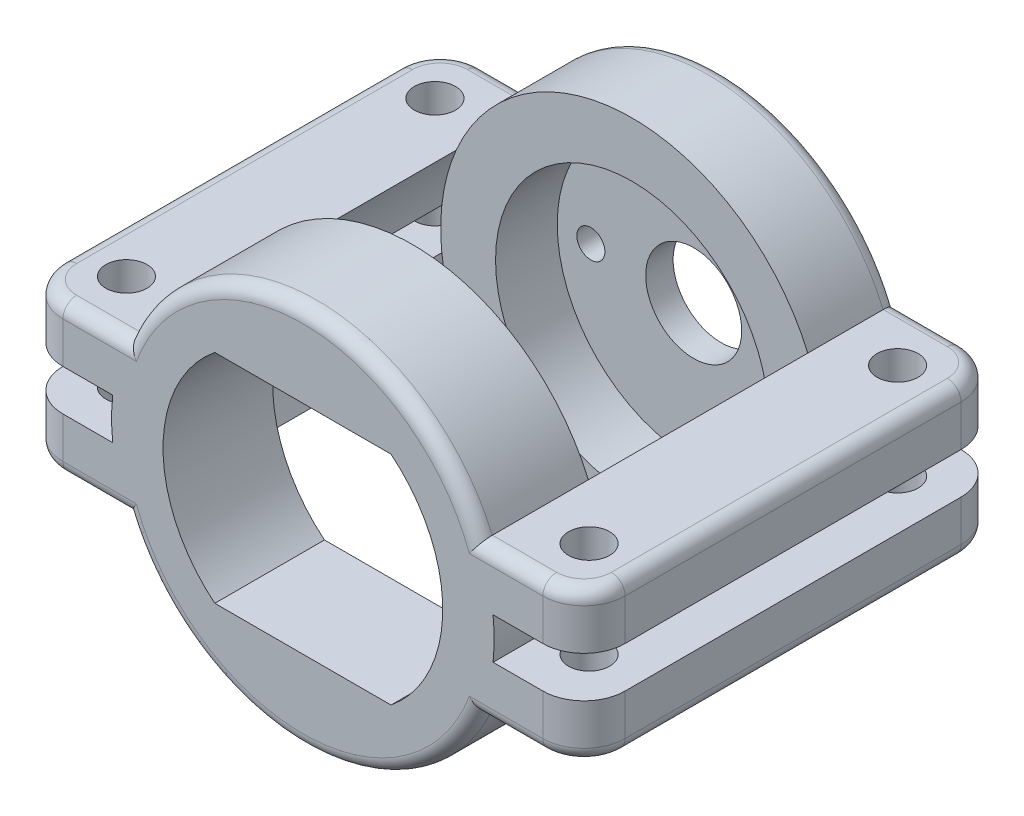
SolidWorks part; units mm, degrees
ref_plane "Alzado" through (0, 0, 0) normal (0, 0, 1) x (1, 0, 0)
ref_plane "Planta" through (0, 0, 0) normal (0, 1, 0) x (1, 0, 0)
ref_plane "Vista lateral" through (0, 0, 0) normal (1, 0, 0) x (0, 0, -1)
sketch "Croquis1" plane through (0, 0, 0) normal (0, 0, 1) x (1, 0, 0)
  line L0 (0, 1.5) -> (0, -1.5) construction
  line L1 (-13.8691, 1.5) -> (-24, 1.5)
  line L2 (-24, 1.5) -> (-24, 5.5)
  line L3 (-13.8691, -1.5) -> (-24, -1.5)
  line L4 (-24, 5.5) -> (-12.82, 5.5)
  line L5 (-24, -1.5) -> (-24, -5.5)
  line L6 (-24, -5.5) -> (-12.82, -5.5)
  line L7 (24, -5.5) -> (12.82, -5.5)
  line L8 (24, 5.5) -> (12.82, 5.5)
  line L9 (13.8691, -1.5) -> (24, -1.5)
  line L10 (13.8691, 1.5) -> (24, 1.5)
  line L11 (24, -1.5) -> (24, -5.5)
  line L12 (24, 1.5) -> (24, 5.5)
  arc A0 (12.82, 5.5) -> (-12.82, 5.5) centre (0, 0) ccw
  arc A1 (-13.8691, 1.5) -> (-13.8691, -1.5) centre (0, 0) ccw
  arc A2 (-12.82, -5.5) -> (12.82, -5.5) centre (0, 0) ccw
  arc A3 (13.8691, -1.5) -> (13.8691, 1.5) centre (0, 0) ccw
  dimension "D2" = 10.1309
  dimension "D3" = 10.1309
  dimension "D4" = 11.18
  dimension "D5" = 11.18
  dimension "D6" = 4
  dimension "D7" = 4
extrude "Saliente-Extruir1" add sketch "Croquis1" along normal blind 6.5
sketch "Croquis2" plane through (0, 0, 6.5) normal (0, 0, 1) x (1, 0, 0)
  circle A0 centre (0, 0) radius 9.95
  dimension "D1" = 19.9
extrude "Cortar-Extruir1" cut sketch "Croquis2" against normal blind 4.5
sketch "Croquis3" plane through (0, 0, 2) normal (0, 0, 1) x (1, 0, 0)
  line L0 (0, 9.95) -> (0, -9.95) construction
  line L1 (-9.95, 0) -> (9.95, 0) construction
  circle A0 centre (0, 0) radius 3.5
  circle A1 centre (0, 0) radius 9.95 construction
  circle A4 centre (-7.5, 0) radius 1.025
  circle A5 centre (7.5, 0) radius 1.025
  dimension "D1" = 7
  dimension "D2" = 2.05
  dimension "D3" = 2.05
  dimension "D4" = 7.5
  dimension "D5" = 7.5
extrude "Cortar-Extruir2" cut sketch "Croquis3" against normal blind 3.5
sketch "Croquis4" plane through (0, 0, 6.5) normal (0, 0, 1) x (1, 0, 0)
  line L2 (-12.82, 5.5) -> (-24, 5.5)
  line L3 (-24, 5.5) -> (-24, 1.5)
  line L4 (-24, 1.5) -> (-13.8691, 1.5)
  line L5 (-13.8691, -1.5) -> (-24, -1.5)
  line L6 (-24, -1.5) -> (-24, -5.5)
  line L7 (-24, -5.5) -> (-12.82, -5.5)
  line L8 (0, 9.95) -> (0, -9.95) construction
  line L9 (24, -5.5) -> (12.82, -5.5)
  line L10 (24, -1.5) -> (24, -5.5)
  line L11 (13.8691, -1.5) -> (24, -1.5)
  line L12 (24, 1.5) -> (13.8691, 1.5)
  line L13 (24, 5.5) -> (24, 1.5)
  line L14 (12.82, 5.5) -> (24, 5.5)
  arc A0 (-12.82, 5.5) -> (-13.8691, 1.5) centre (0, 0) ccw
  arc A1 (12.82, 5.5) -> (-12.82, 5.5) centre (0, 0) ccw construction
  arc A2 (-13.8691, -1.5) -> (-12.82, -5.5) centre (0, 0) ccw
  arc A3 (-13.8691, 1.5) -> (-13.8691, -1.5) centre (0, 0) ccw construction
  circle A4 centre (0, 0) radius 9.95 construction
  arc A5 (13.8691, -1.5) -> (12.82, -5.5) centre (0, 0) cw
  arc A6 (12.82, 5.5) -> (13.8691, 1.5) centre (0, 0) cw
extrude "Saliente-Extruir2" add sketch "Croquis4" along normal blind 16
sketch "Croquis6" plane through (0, 0, 22.5) normal (0, 0, 1) x (1, 0, 0)
  line L0 (-12.82, 5.5) -> (-24, 5.5)
  line L1 (-24, 5.5) -> (-24, 1.5)
  line L2 (-24, 1.5) -> (-13.8691, 1.5)
  line L4 (24, -1.5) -> (13.8691, -1.5)
  line L5 (24, -5.5) -> (24, -1.5)
  line L6 (12.82, 5.5) -> (24, 5.5)
  line L7 (24, 5.5) -> (24, 1.5)
  line L8 (24, 1.5) -> (13.8691, 1.5)
  line L9 (12.82, -5.5) -> (24, -5.5)
  line L10 (-24, -1.5) -> (-13.8691, -1.5)
  line L11 (-24, -5.5) -> (-24, -1.5)
  line L12 (-12.82, -5.5) -> (-24, -5.5)
  arc A0 (12.82, 5.5) -> (-12.82, 5.5) centre (0, 0) ccw
  arc A3 (12.82, -5.5) -> (-12.82, -5.5) centre (0, 0) cw
  arc A4 (-13.8691, 1.5) -> (-13.8691, -1.5) centre (0, 0) ccw
  arc A5 (13.8691, -1.5) -> (13.8691, 1.5) centre (0, 0) ccw
  dimension "D5" = 3
  dimension "D6" = 3
  dimension "D1" = 4
  dimension "D2" = 4
  dimension "D3" = 10.1309
  dimension "D4" = 11.18
  dimension "D7" = 4
  dimension "D8" = 11.18
  dimension "D9" = 4
extrude "Saliente-Extruir3" add sketch "Croquis6" along normal blind 8
sketch "Croquis7" plane through (0, 0, 30.5) normal (0, 0, 1) x (1, 0, 0)
  line L0 (-6.425, 7.9221) -> (6.425, 7.9221)
  line L1 (-6.425, -7.9221) -> (6.425, -7.9221)
  arc A0 (-6.425, 7.9221) -> (-6.425, -7.9221) centre (0, 0) ccw
  arc A1 (6.425, -7.9221) -> (6.425, 7.9221) centre (0, 0) ccw
  dimension "D1" = 10.2
  dimension "D4" = 10.2
  dimension "D2" = 12.85
  dimension "D3" = 12.85
extrude "Cortar-Extruir3" cut sketch "Croquis7" against normal blind 8
sketch "Croquis8" plane through (0, 5.5, 0) normal (0, 1, 0) x (1, 0, 0)
  line L0 (12.82, -30.5) -> (12.82, -22.5) construction
  line L1 (12.82, -22.5) -> (24, -22.5) construction
  line L2 (24, -30.5) -> (24, 0) construction
  line L3 (12.82, 0) -> (12.82, -8) construction
  line L4 (12.82, -22.5) -> (12.82, -6.5) construction
  line L5 (12.82, -8) -> (24, -8) construction
  line L6 (24, 0) -> (12.82, 0) construction
  line L7 (24, -30.5) -> (12.82, -30.5) construction
  line L8 (0, -4) -> (0, -26.5) construction
  circle A0 centre (16.87, -26.5) radius 1.5
  circle A1 centre (16.87, -4) radius 1.5
  circle A2 centre (-16.87, -4) radius 1.5
  circle A3 centre (-16.87, -26.5) radius 1.5
  dimension "D1" = 3
  dimension "D2" = 3
  dimension "D4" = 4.05
  dimension "D3" = 4.05
  dimension "D5" = 4
  dimension "D6" = 4
extrude "Cortar-Extruir4" cut sketch "Croquis8" against normal through all
sketch "Croquis9" plane through (0, 5.5, 0) normal (0, 1, 0) x (1, 0, 0)
  line L0 (0, 0) -> (0, -30.5) construction
  line L1 (24, 0) -> (12.82, 0) construction
  line L2 (24, -30.5) -> (20.5, -30.5)
  line L3 (24, -30.5) -> (24, 0)
  line L4 (24, 0) -> (20.5, 0)
  line L5 (20.5, -30.5) -> (20.5, 0)
  line L6 (-12.82, -30.5) -> (12.82, -30.5) construction
  line L7 (-20.5, -30.5) -> (-20.5, 0)
  line L8 (-24, 0) -> (-20.5, 0)
  line L9 (-24, -30.5) -> (-24, 0)
  line L10 (-24, -30.5) -> (-20.5, -30.5)
  dimension "D1" = 3.5
extrude "Cortar-Extruir6" cut sketch "Croquis9" against normal through all
fillet "Redondeo4" radius 3 8 edges at (20.5, -3.5, 0) (20.5, -3.5, 30.5) (20.5, 3.5, 0) (20.5, 3.5, 30.5) (-20.5, -3.5, 0) (-20.5, -3.5, 30.5) (-20.5, 3.5, 30.5) (-20.5, 3.5, 0)
fillet "Redondeo5" radius 1 24 edges at (-15.16, -5.5, 30.5) (-19.6213, -5.5, 29.6213) (-15.16, -5.5, 0) (-19.6213, -5.5, 0.8787) (-15.16, 5.5, 30.5) (-19.6213, 5.5, 29.6213) (-15.16, 5.5, 0) (-19.6213, 5.5, 0.8787) (15.16, -5.5, 0) (19.6213, -5.5, 0.8787) (15.16, -5.5, 30.5) (19.6213, -5.5, 29.6213) (15.16, 5.5, 0) (19.6213, 5.5, 0.8787) (15.16, 5.5, 30.5) (19.6213, 5.5, 29.6213) (-20.5, -5.5, 15.25) (-20.5, 5.5, 15.25) (20.5, -5.5, 15.25) (20.5, 5.5, 15.25) (0, -13.95, 0) (0, -13.95, 30.5) (0, 13.95, 0) (0, 13.95, 30.5)
